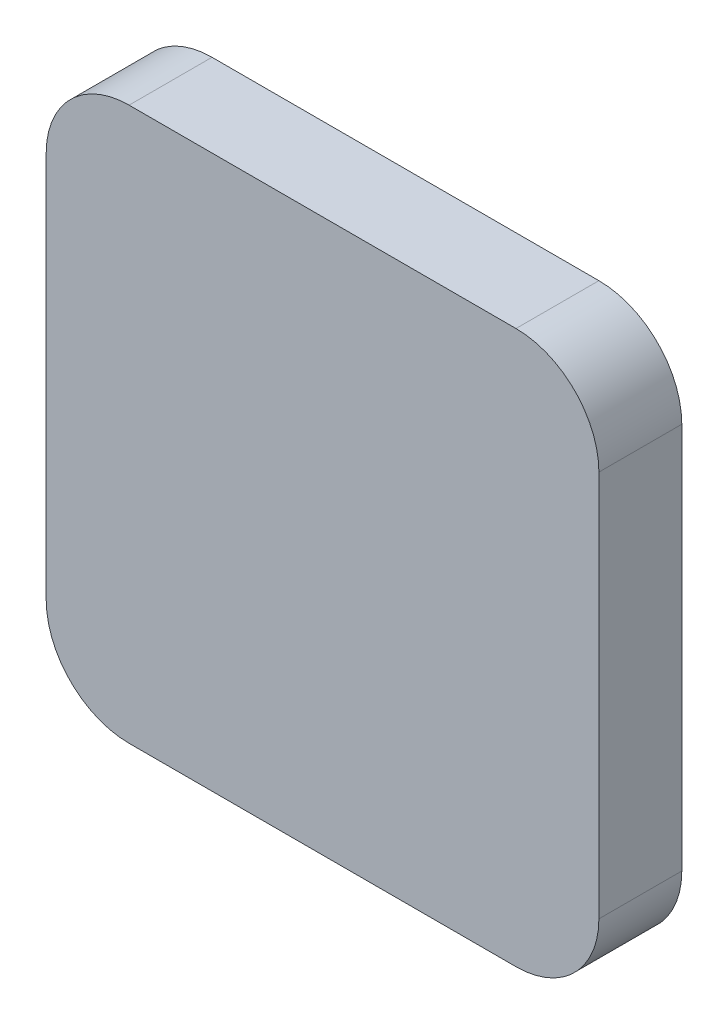
SolidWorks part; units mm, degrees
ref_plane "前视基准面" through (0, 0, 0) normal (0, 0, 1) x (1, 0, 0)
ref_plane "上视基准面" through (0, 0, 0) normal (0, 1, 0) x (1, 0, 0)
ref_plane "右视基准面" through (0, 0, 0) normal (1, 0, 0) x (0, 0, -1)
sketch "草图1" plane through (0, 0, 0) normal (0, 0, 1) x (1, 0, 0)
  line L1 (-7, 10) -> (7, 10)
  line L2 (-10, 7) -> (-10, -7)
  line L3 (-7, -10) -> (7, -10)
  line L4 (10, 7) -> (10, -7)
  line L5 (-10, 10) -> (10, -10) construction
  line L6 (-10, -10) -> (10, 10) construction
  arc A0 (-10, -7) -> (-7, -10) centre (-7, -7) ccw
  arc A1 (7, -10) -> (10, -7) centre (7, -7) ccw
  arc A2 (7, 10) -> (10, 7) centre (7, 7) cw
  arc A3 (-10, 7) -> (-7, 10) centre (-7, 7) cw
  point P0 (0, 0)
  dimension "D2" = 3
  dimension "D1" = 20
extrude "凸台-拉伸1" add sketch "草图1" along normal blind 3
